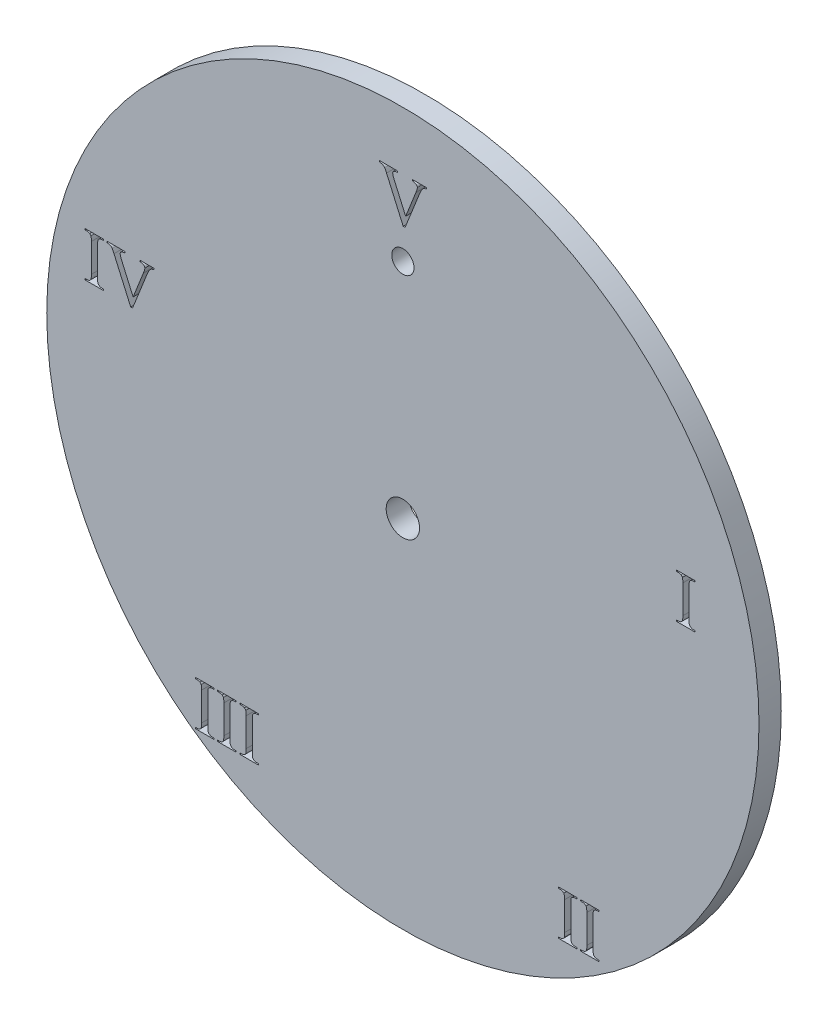
SolidWorks part; units mm, degrees
ref_plane "Front Plane" through (0, 0, 0) normal (0, 0, 1) x (1, 0, 0)
ref_plane "Top Plane" through (0, 0, 0) normal (0, 1, 0) x (1, 0, 0)
ref_plane "Right Plane" through (0, 0, 0) normal (1, 0, 0) x (0, 0, -1)
sketch "Sketch2" plane through (0, 0, 0) normal (0, 0, 1) x (1, 0, 0)
  line L0 (0, 85.09) -> (0, 0) construction
  line L1 (-12.7, 72.39) -> (12.7, 72.39) construction
  line L2 (-12.7, 72.39) -> (-12.7, 97.79) construction
  line L3 (-12.7, 97.79) -> (12.7, 97.79) construction
  line L4 (12.7, 72.39) -> (12.7, 97.79) construction
  line L5 (-12.7, 72.39) -> (12.7, 97.79) construction
  line L6 (-12.7, 97.79) -> (12.7, 72.39) construction
  line L7 (80.9254, 26.2943) -> (0, 0) construction
  line L8 (50.0146, -68.8393) -> (0, 0) construction
  line L9 (-50.0146, -68.8393) -> (0, 0) construction
  line L10 (-80.9254, 26.2943) -> (0, 0) construction
  line L12 (68.2254, 38.9943) -> (93.6254, 38.9943) construction
  line L13 (68.2254, 38.9943) -> (68.2254, 13.5943) construction
  line L14 (68.2254, 13.5943) -> (93.6254, 13.5943) construction
  line L15 (93.6254, 38.9943) -> (93.6254, 13.5943) construction
  line L16 (68.2254, 38.9943) -> (93.6254, 13.5943) construction
  line L17 (68.2254, 13.5943) -> (93.6254, 38.9943) construction
  line L18 (62.7146, -56.1393) -> (37.3146, -56.1393) construction
  line L19 (62.7146, -56.1393) -> (62.7146, -81.5393) construction
  line L20 (62.7146, -81.5393) -> (37.3146, -81.5393) construction
  line L21 (37.3146, -56.1393) -> (37.3146, -81.5393) construction
  line L22 (62.7146, -56.1393) -> (37.3146, -81.5393) construction
  line L23 (62.7146, -81.5393) -> (37.3146, -56.1393) construction
  line L24 (-37.3146, -56.1393) -> (-62.7146, -56.1393) construction
  line L25 (-37.3146, -56.1393) -> (-37.3146, -81.5393) construction
  line L26 (-37.3146, -81.5393) -> (-62.7146, -81.5393) construction
  line L27 (-62.7146, -56.1393) -> (-62.7146, -81.5393) construction
  line L28 (-37.3146, -56.1393) -> (-62.7146, -81.5393) construction
  line L29 (-37.3146, -81.5393) -> (-62.7146, -56.1393) construction
  line L30 (-68.2254, 38.9943) -> (-93.6254, 38.9943) construction
  line L31 (-68.2254, 38.9943) -> (-68.2254, 13.5943) construction
  line L32 (-68.2254, 13.5943) -> (-93.6254, 13.5943) construction
  line L33 (-93.6254, 38.9943) -> (-93.6254, 13.5943) construction
  line L34 (-68.2254, 38.9943) -> (-93.6254, 13.5943) construction
  line L35 (-68.2254, 13.5943) -> (-93.6254, 38.9943) construction
  circle A0 centre (0, 0) radius 101.6
  circle A1 centre (0, 0) radius 4.7625
  circle A2 centre (0, 0) radius 76.2 construction
  circle A3 centre (0, 63.5) radius 3.175
  text T0 "V\r\n" font "Times New Roman" height 12.7
  text T1 "I\r\n\r\n" font "Times New Roman" height 12.7
  text T2 "II" font "Times New Roman" height 12.7
  text T3 "III" font "Times New Roman" height 12.7
  text T4 "IV" font "Times New Roman" height 12.7
  point P4 (0, 85.09)
  point P16 (0, 0)
  dimension "D1" = 203.2
  dimension "D2" = 9.525
  dimension "D7" = 152.4
  dimension "D8" = 6.35
  dimension "D4" = 85.09
  dimension "D5" = 25.4
  dimension "D6" = 25.4
  dimension "D9" = 63.5
  dimension "D3" = 5
extrude "Boss-Extrude1" add sketch "Sketch2" along normal blind 6.35
